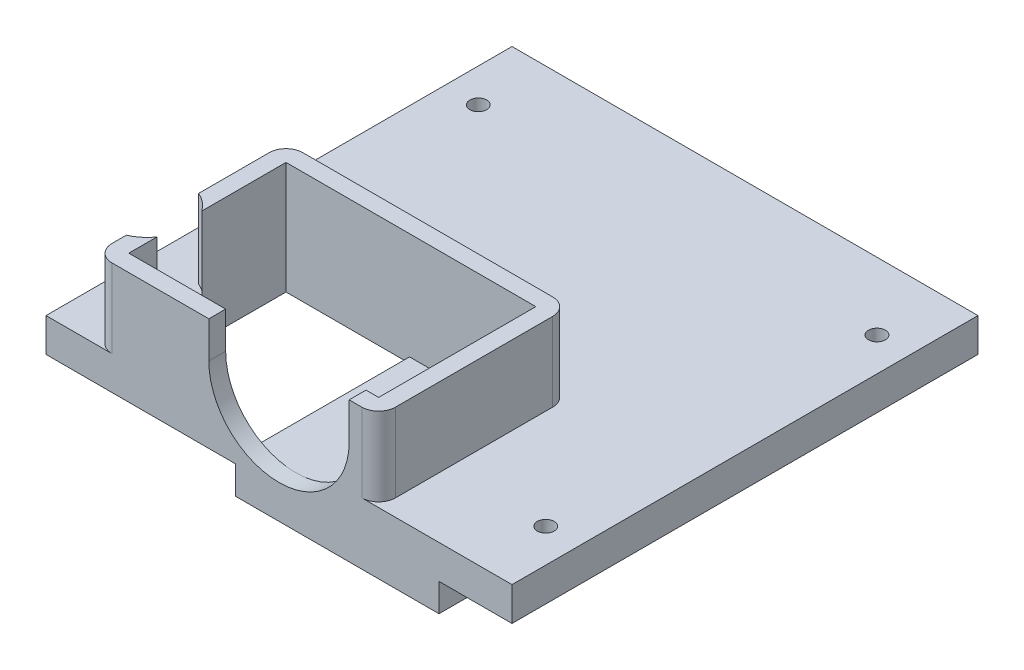
SolidWorks part; units mm, degrees
material "PVB"
ref_plane "Front Plane" through (0, 0, 0) normal (0, 0, 1) x (1, 0, 0)
ref_plane "Top Plane" through (0, 0, 0) normal (0, 1, 0) x (1, 0, 0)
ref_plane "Right Plane" through (0, 0, 0) normal (1, 0, 0) x (0, 0, -1)
sketch "Sketch1" plane through (0, 0, 0) normal (0, 1, 0) x (1, 0, 0)
  line L1 (0, 0) -> (83, 0)
  line L2 (0, 0) -> (0, 83)
  line L3 (0, 83) -> (83, 83)
  line L4 (83, 0) -> (83, 83)
  dimension "D1" = 83
  dimension "D2" = 83
extrude "Boss-Extrude1" add sketch "Sketch1" along normal blind 6
sketch "Sketch2" plane through (0, 6, 0) normal (0, 1, 0) x (1, 0, 0)
  line L0 (83, 83) -> (0, 83) construction
  line L1 (0, 83) -> (0, 0) construction
  line L2 (0, 0) -> (83, 0) construction
  line L3 (83, 0) -> (83, 83) construction
  circle A0 centre (6, 71) radius 1.5
  circle A1 centre (6, 12) radius 1.5
  circle A2 centre (77, 12) radius 1.5
  circle A3 centre (77, 71) radius 1.5
  dimension "D1" = 3
  dimension "D2" = 3
  dimension "D3" = 3
  dimension "D4" = 3
  dimension "D6" = 6
  dimension "D7" = 12
  dimension "D8" = 6
  dimension "D9" = 6
  dimension "D10" = 12
  dimension "D11" = 6
  dimension "D5" = 12
  dimension "D12" = 12
extrude "Cut-Extrude1" cut sketch "Sketch2" against normal through all
ref_plane "Plane1" through (0, 0, -41.5) normal (0, 0, 1) x (1, 0, 0)
sketch "Sketch4" plane through (0, 6, 0) normal (0, 1, 0) x (1, 0, 0)
  line L0 (3, 21) -> (3, 9)
  line L1 (3, 9) -> (13, 9)
  line L2 (13, 15) -> (8, 21)
  line L3 (3, 21) -> (8, 21)
  line L4 (8, 21) -> (13, 15)
  line L5 (13, 15) -> (13, 9)
  line L6 (0, 83) -> (0, 0) construction
  line L7 (0, 0) -> (83, 0) construction
  circle A0 centre (6, 12) radius 1.5
  circle A1 centre (6, 12) radius 1.5 construction
  dimension "D1" = 3
  dimension "D2" = 9
  dimension "D3" = 12
  dimension "D4" = 10
  dimension "D5" = 6
  dimension "D6" = 5
ref_plane "Plane2" through (41.5, 0, 0) normal (-1, 0, 0) x (0, 0, 1)
sketch "Sketch5" plane through (0, 6, 0) normal (0, 1, 0) x (1, 0, 0)
  line L0 (8.75, 34) -> (8.75, 0)
  line L1 (8.75, 34) -> (59.25, 34)
  line L2 (8.75, 0) -> (59.25, 0)
  line L3 (59.25, 34) -> (59.25, 0)
  line L4 (8.75, 34) -> (59.25, 0) construction
  line L5 (8.75, 0) -> (59.25, 34) construction
  line L6 (41.5, 3.3) -> (41.5, -3.3) construction
  line L12 (0, 0) -> (83, 0) construction
  point P1 (34, 17)
  dimension "D1" = 50.5
  dimension "D2" = 34
  dimension "D3" = 7.5
extrude "Boss-Extrude2" add sketch "Sketch5" along normal blind 22
sketch "Sketch6" plane through (0, 28, 0) normal (0, 1, 0) x (1, 0, 0)
  line L14 (56.25, 31) -> (11.75, 31)
  line L15 (11.75, 31) -> (11.75, 3)
  line L16 (11.75, 3) -> (56.25, 3)
  line L17 (56.25, 3) -> (56.25, 31)
  line L18 (56.25, 31) -> (11.75, 31)
  line L19 (11.75, 31) -> (11.75, 3)
  line L20 (11.75, 3) -> (56.25, 3)
  line L21 (56.25, 3) -> (56.25, 31)
  dimension "D1" = 3
extrude "Cut-Extrude5" cut sketch "Sketch6" against normal blind 25
fillet "Fillet1" radius 3 4 edges at (8.75, 17, -34) (59.25, 17, 0) (59.25, 17, -34) (8.75, 17, 0)
sketch "Sketch8" plane through (0, 0, 0) normal (0, 0, 1) x (1, 0, 0)
  line L1 (0, 0) -> (83, 0) construction
  line L3 (59.25, 28) -> (59.25, 6) construction
  circle A0 centre (41.5, 13.5) radius 12.5
  dimension "D2" = 25
  dimension "D1" = 17.75
  dimension "D3" = 13.5
extrude "Cut-Extrude6" cut sketch "Sketch8" against normal blind 10
sketch "Sketch9" plane through (0, 0, 0) normal (0, 0, 1) x (1, 0, 0)
  line L0 (0, 0) -> (83, 0) construction
  line L1 (0, 28) -> (83, 28)
  line L2 (0, 28) -> (0, 20)
  line L3 (0, 20) -> (83, 20)
  line L4 (83, 28) -> (83, 20)
  line L5 (83, 6) -> (83, 0) construction
  line L6 (0, 6) -> (0, 0) construction
  line L7 (11.75, 28) -> (56.25, 28) construction
  dimension "D1" = 20
extrude "Cut-Extrude7" cut sketch "Sketch9" against normal through all both and the other way through all
sketch "Sketch11" plane through (0, 0, 0) normal (0, -1, 0) x (1, 0, 0)
  line L0 (3, -9) -> (13, -9)
  line L1 (13, -9) -> (13, -15)
  line L2 (13, -15) -> (8, -21)
  line L3 (8, -21) -> (3, -21)
  line L4 (3, -21) -> (3, -9)
extrude "Cut-Extrude8" cut sketch "Sketch11" against normal blind 3
mirror "Mirror1" about plane through (0, 0, -41.5) normal (0, 0, 1) of "Cut-Extrude8" second plane through (41.5, 0, 0) second plane normal (-1, 0, 0)
sketch "Sketch13" plane through (0, 20, 0) normal (0, 1, 0) x (1, 0, 0)
  line L12 (52.1771, 0) -> (56.25, 0)
  line L13 (59.25, 3) -> (59.25, 31)
  line L14 (56.25, 34) -> (11.75, 34)
  line L15 (8.75, 31) -> (8.75, 3)
  line L16 (11.75, 0) -> (30.8229, 0)
  line L17 (11.75, 0) -> (30.8229, 0)
  line L18 (30.8229, 0) -> (30.8229, 3)
  line L19 (30.8229, 0) -> (30.8229, 3)
  line L20 (30.8229, 3) -> (11.75, 3)
  line L21 (30.8229, 3) -> (11.75, 3)
  line L22 (11.75, 3) -> (11.75, 31)
  line L23 (11.75, 3) -> (11.75, 31)
  line L24 (52.1771, 0) -> (56.25, 0)
  line L25 (59.25, 3) -> (59.25, 31)
  line L26 (56.25, 34) -> (11.75, 34)
  line L27 (8.75, 31) -> (8.75, 3)
  line L37 (11.75, 31) -> (56.25, 31)
  line L38 (11.75, 31) -> (56.25, 31)
  line L39 (56.25, 31) -> (56.25, 3)
  line L40 (56.25, 31) -> (56.25, 3)
  line L41 (56.25, 3) -> (52.1771, 3)
  line L42 (56.25, 3) -> (52.1771, 3)
  line L43 (52.1771, 3) -> (52.1771, 0)
  line L44 (52.1771, 3) -> (52.1771, 0)
  circle A0 centre (6, 12) radius 1.5 construction
  circle A1 centre (6, 12) radius 1.5
  circle A2 centre (6, 12) radius 7
  arc A11 (56.25, 0) -> (59.25, 3) centre (56.25, 3) ccw
  arc A12 (56.25, 0) -> (59.25, 3) centre (56.25, 3) ccw
  arc A13 (59.25, 31) -> (56.25, 34) centre (56.25, 31) ccw
  arc A14 (59.25, 31) -> (56.25, 34) centre (56.25, 31) ccw
  arc A15 (11.75, 34) -> (8.75, 31) centre (11.75, 31) ccw
  arc A24 (11.75, 34) -> (8.75, 31) centre (11.75, 31) ccw
  arc A25 (8.75, 3) -> (11.75, 0) centre (11.75, 3) ccw
  arc A26 (8.75, 3) -> (11.75, 0) centre (11.75, 3) ccw
  dimension "D2" = 14
  dimension "D1" = 0
extrude "Cut-Extrude9" cut sketch "Sketch13" against normal up to surface (14 mm away) contours L27 A2 L23 up to face at (6, 6, -69.5)
sketch "Sketch14" plane through (0, 0, 0) normal (0, 0, 1) x (1, 0, 0)
  line L0 (29, 13.5) -> (29, 20)
  line L1 (30.8229, 20) -> (11.75, 20) construction
  line L2 (29, 20) -> (30.8229, 20)
  line L3 (30.8229, 20) -> (29, 13.5)
  arc A0 (30.8229, 20) -> (52.1771, 20) centre (41.5, 13.5) ccw construction
extrude "Cut-Extrude10" cut sketch "Sketch14" against normal blind 10
sketch "Sketch15" plane through (0, 0, 0) normal (0, 0, 1) x (1, 0, 0)
  line L0 (54, 20) -> (54, 13.5)
  line L1 (56.25, 20) -> (52.1771, 20) construction
  line L2 (54, 20) -> (52.1771, 20)
  line L3 (52.1771, 20) -> (54, 13.5)
  arc A0 (29, 13.5) -> (52.1771, 20) centre (41.5, 13.5) ccw construction
extrude "Cut-Extrude11" cut sketch "Sketch15" against normal blind 10
sketch "Sketch17" plane through (0, 0, 0) normal (0, -1, 0) x (1, 0, 0)
  line L0 (9.6667, -9) -> (9.6667, -19)
  line L1 (13, -9) -> (3, -9) construction
  line L2 (8, -21) -> (13, -15) construction
  line L3 (9.6667, -19) -> (13, -15)
  line L4 (13, -15) -> (13, -9)
  line L5 (13, -9) -> (9.6667, -9)
  dimension "D1" = 10
extrude "Boss-Extrude3" add sketch "Sketch17" against normal up to surface (3 mm away) up to face at (7.5, 3, -15.3)
sketch "Sketch18" plane through (0, 3, 0) normal (0, 1, 0) x (1, 0, 0)
  line L8 (34.7177, 3) -> (34.7177, 10)
  line L9 (34.7177, 10) -> (48.2823, 10)
  line L10 (48.2823, 10) -> (48.2823, 3)
  line L11 (48.2823, 3) -> (56.25, 3)
  line L12 (56.25, 3) -> (56.25, 31)
  line L13 (56.25, 31) -> (11.75, 31)
  line L14 (11.75, 31) -> (11.75, 3)
  line L15 (11.75, 3) -> (34.7177, 3)
extrude "Cut-Extrude14" cut sketch "Sketch18" against normal blind 4
sketch "Sketch20" plane through (0, 0, 0) normal (0, -1, 0) x (1, 0, 0)
  line L1 (34.7177, -10) -> (48.2823, -10)
  line L2 (34.7177, -10) -> (34.7177, -3)
  line L3 (34.7177, -3) -> (48.2823, -3)
  line L4 (48.2823, -10) -> (48.2823, -3)
extrude "Cut-Extrude15" cut sketch "Sketch20" against normal blind 4
sketch "Sketch21" plane through (0, 0, 0) normal (0, -1, 0) x (1, 0, 0)
  line L0 (0, 0) -> (83, 0) construction
  line L1 (33.75, 0) -> (70, 0)
  line L2 (33.75, 0) -> (33.75, -37)
  line L3 (33.75, -37) -> (70, -37)
  line L4 (70, 0) -> (70, -37)
  line L5 (70, -15) -> (70, -9) construction
  line L8 (11.75, -3) -> (11.75, -31) construction
  line L9 (11.75, -31) -> (56.25, -31) construction
  dimension "D1" = 22
  dimension "D2" = 6
extrude "Boss-Extrude4" add sketch "Sketch21" along normal blind 5 and the other way blind 1
fillet "Fillet2" radius 5 2 edges at (70, -2.5, -37) (33.75, -2.5, -37)
